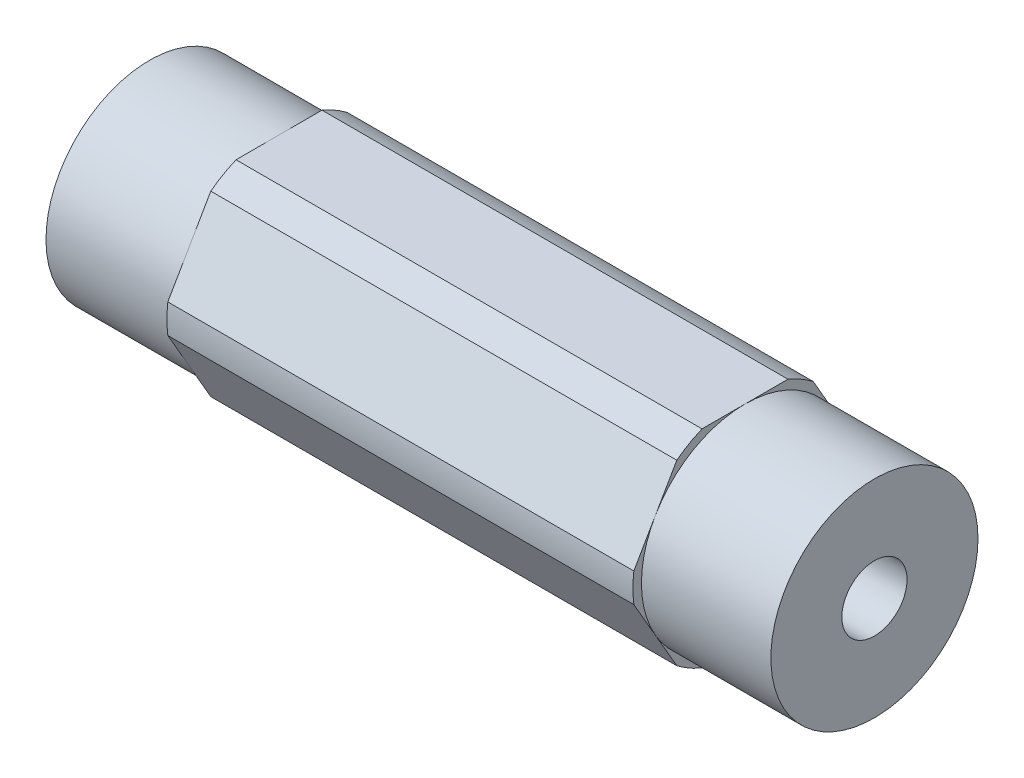
SolidWorks part; units mm, degrees
material "6061-T6 (SS)"
ref_plane "Front Plane" through (0, 0, 0) normal (0, 0, 1) x (1, 0, 0)
ref_plane "Top Plane" through (0, 0, 0) normal (0, 1, 0) x (1, 0, 0)
ref_plane "Right Plane" through (0, 0, 0) normal (1, 0, 0) x (0, 0, -1)
sketch "Sketch1" plane through (0, 0, 0) normal (1, 0, 0) x (0, 0, -1)
  line L1 (7.3323, 0) -> (3.6662, 6.35)
  line L2 (3.6662, 6.35) -> (-3.6662, 6.35)
  line L3 (-3.6662, 6.35) -> (-7.3323, 0)
  line L4 (-7.3323, 0) -> (-3.6662, -6.35)
  line L5 (-3.6662, -6.35) -> (3.6662, -6.35)
  line L6 (3.6662, -6.35) -> (7.3323, 0)
  circle A0 centre (0, 0) radius 6.35 construction
  circle A1 centre (0, 0) radius 6.875
  circle A2 centre (0, 0) radius 2
  dimension "D1" = 12.7
  dimension "D2" = 13.75
  dimension "D3" = 4
extrude "Boss-Extrude1" add sketch "Sketch1" along normal mid plane 44.45 contours L1 A1 L2 L3 L4 L5 L6
ref_plane "Plane1" through (0, 0, 0) normal (-1, 0, 0) x (0, 0, 1)
sketch "Sketch4" plane through (-22.225, 0, 0) normal (-1, 0, 0) x (0, 0, 1)
  circle A0 centre (0, 0) radius 6.35
  dimension "D1" = 12.7
extrude "Cut-Extrude-Thin1" cut sketch "Sketch4" against normal blind 7.9375 thin
mirror "Mirror1" about plane through (0, 0, 0) normal (-1, 0, 0) of "Cut-Extrude-Thin1"
equation "\"D2@Sketch1\"=13.75mm"
equation "\"D3@Sketch1\"=4mm"
